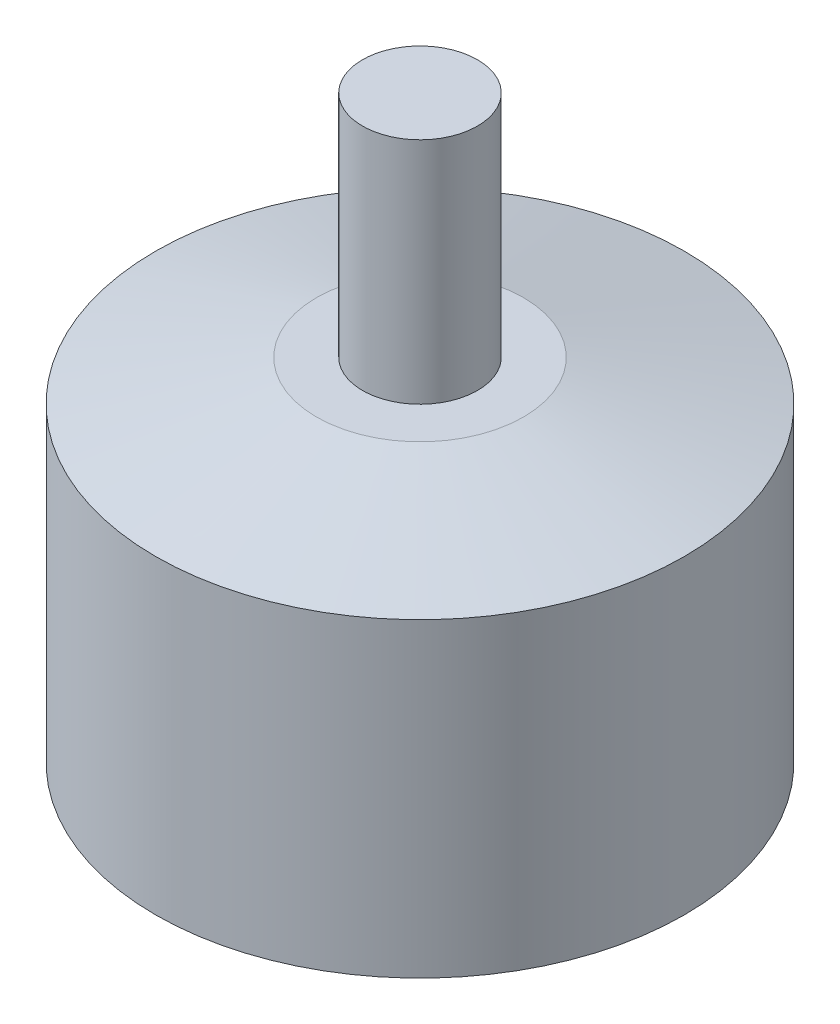
SolidWorks part; units mm, degrees
ref_plane "Front Plane" through (0, 0, 0) normal (0, 0, 1) x (1, 0, 0)
ref_plane "Top Plane" through (0, 0, 0) normal (0, 1, 0) x (1, 0, 0)
ref_plane "Right Plane" through (0, 0, 0) normal (1, 0, 0) x (0, 0, -1)
sketch "Sketch2" plane through (0, 0, 0) normal (0, 0, 1) x (1, 0, 0)
  line L0 (-11.5, 13.5) -> (-4.5, 15.25)
  line L1 (0, 0) -> (-11.5, 0)
  line L2 (0, 0) -> (0, 13.5)
  line L3 (0, 13.5) -> (-11.5, 13.5)
  line L4 (-11.5, 0) -> (-11.5, 13.5)
  line L5 (0, 13.5) -> (-4.5, 13.5)
  line L6 (0, 13.5) -> (0, 15.25)
  line L7 (0, 15.25) -> (-4.5, 15.25)
  line L8 (-4.5, 13.5) -> (-4.5, 15.25)
  line L9 (0, 15.25) -> (-2.5, 15.25)
  line L10 (0, 15.25) -> (0, 25.2106)
  line L11 (0, 25.2106) -> (-2.5, 25.2106)
  line L12 (-2.5, 15.25) -> (-2.5, 25.2106)
  dimension "D1" = 13.5
  dimension "D2" = 11.5
  dimension "D3" = 4.5
  dimension "D4" = 1.75
  dimension "D5" = 2.5
revolve "Revolve1" add sketch "Sketch2" angle 360 about L10
